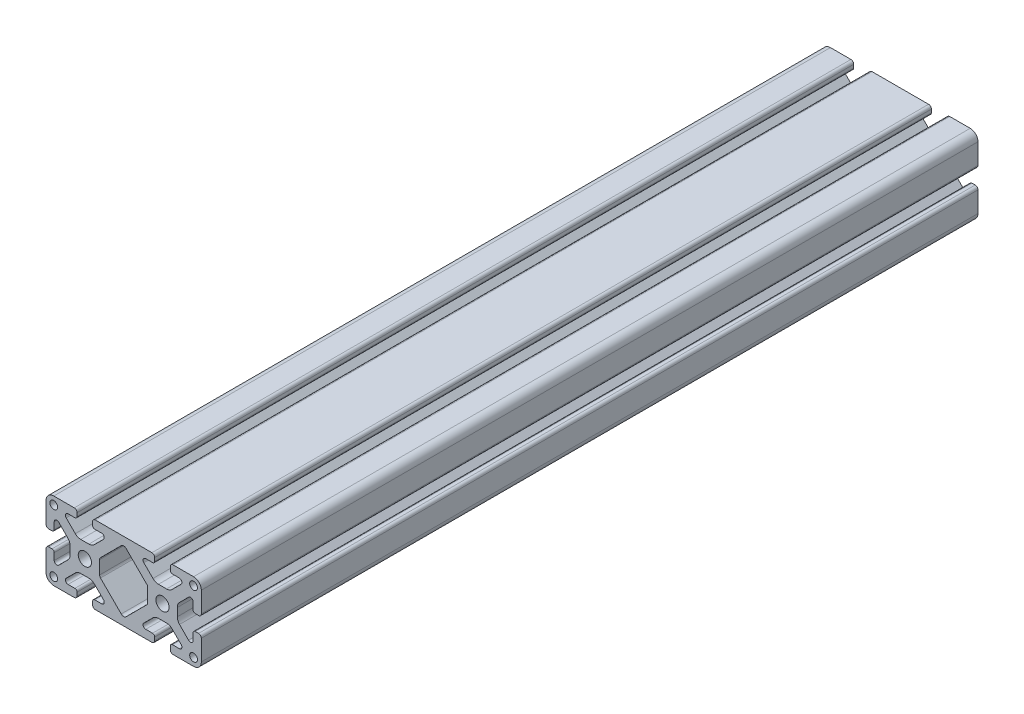
SolidWorks part; units mm, degrees
ref_plane "Front" through (0, 0, 0) normal (0, 0, 1) x (1, 0, 0)
ref_plane "Top" through (0, 0, 0) normal (0, 1, 0) x (1, 0, 0)
ref_plane "Right" through (0, 0, 0) normal (1, 0, 0) x (0, 0, -1)
sketch "Support-Front" plane through (0, 0, 0) normal (0, 0, 1) x (1, 0, 0)
  line L0 (50, 0) -> (-50, 0) construction
  line L1 (-50, -25) -> (50, -25)
  line L2 (-50, -25) -> (-50, 25)
  line L3 (-50, 25) -> (50, 25)
  line L4 (50, -25) -> (50, 25)
  line L5 (0, 25) -> (0, -25) construction
  dimension "Height-Profile" = 50
  dimension "Width-Profile" = 100
sketch "Support-Right-Length" plane through (0, 0, 0) normal (1, 0, 0) x (0, 0, -1)
  line L0 (0, -25) -> (0, 25) construction
  line L1 (-250, 25) -> (250, 25)
  line L2 (-250, 25) -> (-250, -25)
  line L3 (-250, -25) -> (250, -25)
  line L4 (250, 25) -> (250, -25)
  dimension "Length-Profile" = 500
sketch "Support-Profile" plane through (0, 0, 0) normal (0, 0, 1) x (1, 0, 0)
  line L12 (-14.9142, -5.6858) -> (-1.5556, -19.0444)
  line L13 (-15.5, 4.2716) -> (-15.5, -4.2716)
  line L14 (-1.5556, 19.0444) -> (-14.9142, 5.6858)
  line L15 (14.9142, 5.6858) -> (1.5556, 19.0444)
  line L16 (15.5, -4.2716) -> (15.5, 4.2716)
  line L17 (1.5556, -19.0444) -> (14.9142, -5.6858)
  line L104 (-30, -23.2) -> (-30, -21.1)
  line L105 (-31.4, -19.7) -> (-35.8, -19.7)
  line L106 (-36.9987, -16.7945) -> (-31.1255, -10.9545)
  line L107 (-27.6, -9.5) -> (-22.4, -9.5)
  line L108 (-18.8745, -10.9545) -> (-13.0013, -16.7945)
  line L109 (-14.2, -19.7) -> (-18.6, -19.7)
  line L110 (-20, -21.1) -> (-20, -23.2)
  line L111 (-18.2, -25) -> (18.2, -25)
  line L112 (20, -23.2) -> (20, -21.1)
  line L113 (18.6, -19.7) -> (14.2, -19.7)
  line L114 (13.0013, -16.7945) -> (18.8745, -10.9545)
  line L115 (22.4, -9.5) -> (27.6, -9.5)
  line L116 (31.1255, -10.9545) -> (36.9987, -16.7945)
  line L117 (35.8, -19.7) -> (31.4, -19.7)
  line L118 (30, -21.1) -> (30, -23.2)
  line L119 (31.8, -25) -> (45, -25)
  line L120 (50, -20) -> (50, -6.8)
  line L121 (48.2, -5) -> (46.1, -5)
  line L122 (44.7, -6.4) -> (44.7, -10.8)
  line L123 (41.7945, -11.9987) -> (35.9545, -6.1255)
  line L124 (34.5, -2.6) -> (34.5, 2.6)
  line L125 (35.9545, 6.1255) -> (41.7945, 11.9987)
  line L126 (44.7, 10.8) -> (44.7, 6.4)
  line L127 (46.1, 5) -> (48.2, 5)
  line L128 (50, 6.8) -> (50, 20)
  line L129 (45, 25) -> (31.8, 25)
  line L130 (30, 23.2) -> (30, 21.1)
  line L131 (31.4, 19.7) -> (35.8, 19.7)
  line L132 (36.9987, 16.7945) -> (31.1255, 10.9545)
  line L133 (27.6, 9.5) -> (22.4, 9.5)
  line L134 (18.8745, 10.9545) -> (13.0013, 16.7945)
  line L135 (14.2, 19.7) -> (18.6, 19.7)
  line L136 (20, 21.1) -> (20, 23.2)
  line L137 (18.2, 25) -> (-18.2, 25)
  line L138 (-20, 23.2) -> (-20, 21.1)
  line L139 (-18.6, 19.7) -> (-14.2, 19.7)
  line L140 (-13.0013, 16.7945) -> (-18.8745, 10.9545)
  line L141 (-22.4, 9.5) -> (-27.6, 9.5)
  line L142 (-31.1255, 10.9545) -> (-36.9987, 16.7945)
  line L143 (-35.8, 19.7) -> (-31.4, 19.7)
  line L144 (-30, 21.1) -> (-30, 23.2)
  line L145 (-31.8, 25) -> (-45, 25)
  line L146 (-50, 20) -> (-50, 6.8)
  line L147 (-48.2, 5) -> (-46.1, 5)
  line L148 (-44.7, 6.4) -> (-44.7, 10.8)
  line L149 (-41.7945, 11.9987) -> (-35.9545, 6.1255)
  line L150 (-34.5, 2.6) -> (-34.5, -2.6)
  line L151 (-35.9545, -6.1255) -> (-41.7945, -11.9987)
  line L152 (-44.7, -10.8) -> (-44.7, -6.4)
  line L153 (-46.1, -5) -> (-48.2, -5)
  line L154 (-50, -6.8) -> (-50, -20)
  line L155 (-45, -25) -> (-31.8, -25)
  circle A1 centre (-25, 0) radius 4.25
  circle A3 centre (-45, 20) radius 2.5
  circle A5 centre (-45, -20) radius 2.5
  arc A12 (-15.5, -4.2716) -> (-14.9142, -5.6858) centre (-13.5, -4.2716) ccw
  arc A13 (-14.9142, 5.6858) -> (-15.5, 4.2716) centre (-13.5, 4.2716) ccw
  arc A14 (1.5556, 19.0444) -> (-1.5556, 19.0444) centre (0, 17.4887) ccw
  arc A15 (15.5, 4.2716) -> (14.9142, 5.6858) centre (13.5, 4.2716) ccw
  arc A16 (14.9142, -5.6858) -> (15.5, -4.2716) centre (13.5, -4.2716) ccw
  arc A17 (-1.5556, -19.0444) -> (1.5556, -19.0444) centre (0, -17.4887) ccw
  circle A19 centre (25, 0) radius 4.25
  circle A21 centre (45, -20) radius 2.5
  circle A23 centre (45, 20) radius 2.5
  arc A104 (-30, -21.1) -> (-31.4, -19.7) centre (-31.4, -21.1) ccw
  arc A105 (-36.9987, -16.7945) -> (-35.8, -19.7) centre (-35.8, -18) ccw
  arc A106 (-27.6, -9.5) -> (-31.1255, -10.9545) centre (-27.6, -14.5) ccw
  arc A107 (-18.8745, -10.9545) -> (-22.4, -9.5) centre (-22.4, -14.5) ccw
  arc A108 (-14.2, -19.7) -> (-13.0013, -16.7945) centre (-14.2, -18) ccw
  arc A109 (-18.6, -19.7) -> (-20, -21.1) centre (-18.6, -21.1) ccw
  arc A110 (-20, -23.2) -> (-18.2, -25) centre (-18.2, -23.2) ccw
  arc A111 (18.2, -25) -> (20, -23.2) centre (18.2, -23.2) ccw
  arc A112 (20, -21.1) -> (18.6, -19.7) centre (18.6, -21.1) ccw
  arc A113 (13.0013, -16.7945) -> (14.2, -19.7) centre (14.2, -18) ccw
  arc A114 (22.4, -9.5) -> (18.8745, -10.9545) centre (22.4, -14.5) ccw
  arc A115 (31.1255, -10.9545) -> (27.6, -9.5) centre (27.6, -14.5) ccw
  arc A116 (35.8, -19.7) -> (36.9987, -16.7945) centre (35.8, -18) ccw
  arc A117 (31.4, -19.7) -> (30, -21.1) centre (31.4, -21.1) ccw
  arc A118 (30, -23.2) -> (31.8, -25) centre (31.8, -23.2) ccw
  arc A119 (45, -25) -> (50, -20) centre (45, -20) ccw
  arc A120 (50, -6.8) -> (48.2, -5) centre (48.2, -6.8) ccw
  arc A121 (46.1, -5) -> (44.7, -6.4) centre (46.1, -6.4) ccw
  arc A122 (41.7945, -11.9987) -> (44.7, -10.8) centre (43, -10.8) ccw
  arc A123 (34.5, -2.6) -> (35.9545, -6.1255) centre (39.5, -2.6) ccw
  arc A124 (35.9545, 6.1255) -> (34.5, 2.6) centre (39.5, 2.6) ccw
  arc A125 (44.7, 10.8) -> (41.7945, 11.9987) centre (43, 10.8) ccw
  arc A126 (44.7, 6.4) -> (46.1, 5) centre (46.1, 6.4) ccw
  arc A127 (48.2, 5) -> (50, 6.8) centre (48.2, 6.8) ccw
  arc A128 (50, 20) -> (45, 25) centre (45, 20) ccw
  arc A129 (31.8, 25) -> (30, 23.2) centre (31.8, 23.2) ccw
  arc A130 (30, 21.1) -> (31.4, 19.7) centre (31.4, 21.1) ccw
  arc A131 (36.9987, 16.7945) -> (35.8, 19.7) centre (35.8, 18) ccw
  arc A132 (27.6, 9.5) -> (31.1255, 10.9545) centre (27.6, 14.5) ccw
  arc A133 (18.8745, 10.9545) -> (22.4, 9.5) centre (22.4, 14.5) ccw
  arc A134 (14.2, 19.7) -> (13.0013, 16.7945) centre (14.2, 18) ccw
  arc A135 (18.6, 19.7) -> (20, 21.1) centre (18.6, 21.1) ccw
  arc A136 (20, 23.2) -> (18.2, 25) centre (18.2, 23.2) ccw
  arc A137 (-18.2, 25) -> (-20, 23.2) centre (-18.2, 23.2) ccw
  arc A138 (-20, 21.1) -> (-18.6, 19.7) centre (-18.6, 21.1) ccw
  arc A139 (-13.0013, 16.7945) -> (-14.2, 19.7) centre (-14.2, 18) ccw
  arc A140 (-22.4, 9.5) -> (-18.8745, 10.9545) centre (-22.4, 14.5) ccw
  arc A141 (-31.1255, 10.9545) -> (-27.6, 9.5) centre (-27.6, 14.5) ccw
  arc A142 (-35.8, 19.7) -> (-36.9987, 16.7945) centre (-35.8, 18) ccw
  arc A143 (-31.4, 19.7) -> (-30, 21.1) centre (-31.4, 21.1) ccw
  arc A144 (-30, 23.2) -> (-31.8, 25) centre (-31.8, 23.2) ccw
  arc A145 (-45, 25) -> (-50, 20) centre (-45, 20) ccw
  arc A146 (-50, 6.8) -> (-48.2, 5) centre (-48.2, 6.8) ccw
  arc A147 (-46.1, 5) -> (-44.7, 6.4) centre (-46.1, 6.4) ccw
  arc A148 (-41.7945, 11.9987) -> (-44.7, 10.8) centre (-43, 10.8) ccw
  arc A149 (-34.5, 2.6) -> (-35.9545, 6.1255) centre (-39.5, 2.6) ccw
  arc A150 (-35.9545, -6.1255) -> (-34.5, -2.6) centre (-39.5, -2.6) ccw
  arc A151 (-44.7, -10.8) -> (-41.7945, -11.9987) centre (-43, -10.8) ccw
  arc A152 (-44.7, -6.4) -> (-46.1, -5) centre (-46.1, -6.4) ccw
  arc A153 (-48.2, -5) -> (-50, -6.8) centre (-48.2, -6.8) ccw
  arc A154 (-50, -20) -> (-45, -25) centre (-45, -20) ccw
  arc A155 (-31.8, -25) -> (-30, -23.2) centre (-31.8, -23.2) ccw
ref_plane "Ref-Plane-1" through (0, 0, 250) normal (0, 0, 1) x (1, 0, 0)
ref_plane "Ref-Plane-2" through (0, 0, -250) normal (0, 0, 1) x (1, 0, 0)
sketch "Sketch4" plane through (0, 0, 250) normal (0, 0, 1) x (1, 0, 0)
  line L0 (-50, -25) -> (-50, 25) construction
  line L1 (-50, -25) -> (50, -25) construction
  line L2 (50, -25) -> (50, 25) construction
  line L3 (-50, 25) -> (50, 25) construction
  line L4 (-50, -25) -> (-50, 25)
  line L5 (-50, -25) -> (50, -25)
  line L6 (50, -25) -> (50, 25)
  line L7 (-50, 25) -> (50, 25)
extrude "Body" add sketch "Sketch4" against normal up to surface (500 mm away) up to plane "Ref-Plane-2"
sketch "Sketch6" plane through (0, 0, 0) normal (0, 0, 1) x (1, 0, 0)
  line L6 (14.9142, 5.6858) -> (1.5556, 19.0444)
  line L7 (-1.5556, 19.0444) -> (-14.9142, 5.6858)
  line L8 (-15.5, 4.2716) -> (-15.5, -4.2716)
  line L9 (-14.9142, -5.6858) -> (-1.5556, -19.0444)
  line L10 (1.5556, -19.0444) -> (14.9142, -5.6858)
  line L11 (15.5, -4.2716) -> (15.5, 4.2716)
  line L12 (14.9142, 5.6858) -> (1.5556, 19.0444)
  line L13 (-1.5556, 19.0444) -> (-14.9142, 5.6858)
  line L14 (-15.5, 4.2716) -> (-15.5, -4.2716)
  line L15 (-14.9142, -5.6858) -> (-1.5556, -19.0444)
  line L16 (1.5556, -19.0444) -> (14.9142, -5.6858)
  line L17 (15.5, -4.2716) -> (15.5, 4.2716)
  line L52 (-31.4, -19.7) -> (-35.8, -19.7)
  line L53 (-36.9987, -16.7945) -> (-31.1255, -10.9545)
  line L54 (-27.6, -9.5) -> (-22.4, -9.5)
  line L55 (-18.8745, -10.9545) -> (-13.0013, -16.7945)
  line L56 (-14.2, -19.7) -> (-18.6, -19.7)
  line L57 (-20, -21.1) -> (-20, -23.2)
  line L58 (-18.2, -25) -> (18.2, -25)
  line L59 (20, -23.2) -> (20, -21.1)
  line L60 (18.6, -19.7) -> (14.2, -19.7)
  line L61 (13.0013, -16.7945) -> (18.8745, -10.9545)
  line L62 (22.4, -9.5) -> (27.6, -9.5)
  line L63 (31.1255, -10.9545) -> (36.9987, -16.7945)
  line L64 (35.8, -19.7) -> (31.4, -19.7)
  line L65 (30, -21.1) -> (30, -23.2)
  line L66 (31.8, -25) -> (45, -25)
  line L67 (50, -20) -> (50, -6.8)
  line L68 (48.2, -5) -> (46.1, -5)
  line L69 (44.7, -6.4) -> (44.7, -10.8)
  line L70 (41.7945, -11.9987) -> (35.9545, -6.1255)
  line L71 (34.5, -2.6) -> (34.5, 2.6)
  line L72 (35.9545, 6.1255) -> (41.7945, 11.9987)
  line L73 (44.7, 10.8) -> (44.7, 6.4)
  line L74 (46.1, 5) -> (48.2, 5)
  line L75 (50, 6.8) -> (50, 20)
  line L76 (45, 25) -> (31.8, 25)
  line L77 (30, 23.2) -> (30, 21.1)
  line L78 (31.4, 19.7) -> (35.8, 19.7)
  line L79 (36.9987, 16.7945) -> (31.1255, 10.9545)
  line L80 (27.6, 9.5) -> (22.4, 9.5)
  line L81 (18.8745, 10.9545) -> (13.0013, 16.7945)
  line L82 (14.2, 19.7) -> (18.6, 19.7)
  line L83 (20, 21.1) -> (20, 23.2)
  line L84 (18.2, 25) -> (-18.2, 25)
  line L85 (-20, 23.2) -> (-20, 21.1)
  line L86 (-18.6, 19.7) -> (-14.2, 19.7)
  line L87 (-13.0013, 16.7945) -> (-18.8745, 10.9545)
  line L88 (-22.4, 9.5) -> (-27.6, 9.5)
  line L89 (-31.1255, 10.9545) -> (-36.9987, 16.7945)
  line L90 (-35.8, 19.7) -> (-31.4, 19.7)
  line L91 (-30, 21.1) -> (-30, 23.2)
  line L92 (-31.8, 25) -> (-45, 25)
  line L93 (-50, 20) -> (-50, 6.8)
  line L94 (-48.2, 5) -> (-46.1, 5)
  line L95 (-44.7, 6.4) -> (-44.7, 10.8)
  line L96 (-41.7945, 11.9987) -> (-35.9545, 6.1255)
  line L97 (-34.5, 2.6) -> (-34.5, -2.6)
  line L98 (-35.9545, -6.1255) -> (-41.7945, -11.9987)
  line L99 (-44.7, -10.8) -> (-44.7, -6.4)
  line L100 (-46.1, -5) -> (-48.2, -5)
  line L101 (-50, -6.8) -> (-50, -20)
  line L102 (-45, -25) -> (-31.8, -25)
  line L103 (-30, -23.2) -> (-30, -21.1)
  line L104 (-31.4, -19.7) -> (-35.8, -19.7)
  line L105 (-36.9987, -16.7945) -> (-31.1255, -10.9545)
  line L106 (-27.6, -9.5) -> (-22.4, -9.5)
  line L107 (-18.8745, -10.9545) -> (-13.0013, -16.7945)
  line L108 (-14.2, -19.7) -> (-18.6, -19.7)
  line L109 (-20, -21.1) -> (-20, -23.2)
  line L110 (-18.2, -25) -> (18.2, -25)
  line L111 (20, -23.2) -> (20, -21.1)
  line L112 (18.6, -19.7) -> (14.2, -19.7)
  line L113 (13.0013, -16.7945) -> (18.8745, -10.9545)
  line L114 (22.4, -9.5) -> (27.6, -9.5)
  line L115 (31.1255, -10.9545) -> (36.9987, -16.7945)
  line L116 (35.8, -19.7) -> (31.4, -19.7)
  line L117 (30, -21.1) -> (30, -23.2)
  line L118 (31.8, -25) -> (45, -25)
  line L119 (50, -20) -> (50, -6.8)
  line L120 (48.2, -5) -> (46.1, -5)
  line L121 (44.7, -6.4) -> (44.7, -10.8)
  line L122 (41.7945, -11.9987) -> (35.9545, -6.1255)
  line L123 (34.5, -2.6) -> (34.5, 2.6)
  line L124 (35.9545, 6.1255) -> (41.7945, 11.9987)
  line L125 (44.7, 10.8) -> (44.7, 6.4)
  line L126 (46.1, 5) -> (48.2, 5)
  line L127 (50, 6.8) -> (50, 20)
  line L128 (45, 25) -> (31.8, 25)
  line L129 (30, 23.2) -> (30, 21.1)
  line L130 (31.4, 19.7) -> (35.8, 19.7)
  line L131 (36.9987, 16.7945) -> (31.1255, 10.9545)
  line L132 (27.6, 9.5) -> (22.4, 9.5)
  line L133 (18.8745, 10.9545) -> (13.0013, 16.7945)
  line L134 (14.2, 19.7) -> (18.6, 19.7)
  line L135 (20, 21.1) -> (20, 23.2)
  line L136 (18.2, 25) -> (-18.2, 25)
  line L137 (-20, 23.2) -> (-20, 21.1)
  line L138 (-18.6, 19.7) -> (-14.2, 19.7)
  line L139 (-13.0013, 16.7945) -> (-18.8745, 10.9545)
  line L140 (-22.4, 9.5) -> (-27.6, 9.5)
  line L141 (-31.1255, 10.9545) -> (-36.9987, 16.7945)
  line L142 (-35.8, 19.7) -> (-31.4, 19.7)
  line L143 (-30, 21.1) -> (-30, 23.2)
  line L144 (-31.8, 25) -> (-45, 25)
  line L145 (-50, 20) -> (-50, 6.8)
  line L146 (-48.2, 5) -> (-46.1, 5)
  line L147 (-44.7, 6.4) -> (-44.7, 10.8)
  line L148 (-41.7945, 11.9987) -> (-35.9545, 6.1255)
  line L149 (-34.5, 2.6) -> (-34.5, -2.6)
  line L150 (-35.9545, -6.1255) -> (-41.7945, -11.9987)
  line L151 (-44.7, -10.8) -> (-44.7, -6.4)
  line L152 (-46.1, -5) -> (-48.2, -5)
  line L153 (-50, -6.8) -> (-50, -20)
  line L154 (-45, -25) -> (-31.8, -25)
  line L155 (-30, -23.2) -> (-30, -21.1)
  circle A0 centre (25, 0) radius 4.25 construction
  circle A1 centre (45, -20) radius 2.5 construction
  circle A2 centre (45, 20) radius 2.5 construction
  circle A3 centre (-45, -20) radius 2.5 construction
  circle A4 centre (-45, 20) radius 2.5 construction
  circle A5 centre (-25, 0) radius 4.25 construction
  circle A6 centre (25, 0) radius 4.25
  circle A7 centre (45, -20) radius 2.5
  circle A8 centre (45, 20) radius 2.5
  circle A9 centre (-45, -20) radius 2.5
  circle A10 centre (-45, 20) radius 2.5
  circle A11 centre (-25, 0) radius 4.25
  arc A18 (1.5556, 19.0444) -> (-1.5556, 19.0444) centre (0, 17.4887) ccw
  arc A19 (-14.9142, 5.6858) -> (-15.5, 4.2716) centre (-13.5, 4.2716) ccw
  arc A20 (-15.5, -4.2716) -> (-14.9142, -5.6858) centre (-13.5, -4.2716) ccw
  arc A21 (-1.5556, -19.0444) -> (1.5556, -19.0444) centre (0, -17.4887) ccw
  arc A22 (14.9142, -5.6858) -> (15.5, -4.2716) centre (13.5, -4.2716) ccw
  arc A23 (15.5, 4.2716) -> (14.9142, 5.6858) centre (13.5, 4.2716) ccw
  arc A24 (1.5556, 19.0444) -> (-1.5556, 19.0444) centre (0, 17.4887) ccw
  arc A25 (-14.9142, 5.6858) -> (-15.5, 4.2716) centre (-13.5, 4.2716) ccw
  arc A26 (-15.5, -4.2716) -> (-14.9142, -5.6858) centre (-13.5, -4.2716) ccw
  arc A27 (-1.5556, -19.0444) -> (1.5556, -19.0444) centre (0, -17.4887) ccw
  arc A28 (14.9142, -5.6858) -> (15.5, -4.2716) centre (13.5, -4.2716) ccw
  arc A29 (15.5, 4.2716) -> (14.9142, 5.6858) centre (13.5, 4.2716) ccw
  arc A52 (-36.9987, -16.7945) -> (-35.8, -19.7) centre (-35.8, -18) ccw
  arc A53 (-27.6, -9.5) -> (-31.1255, -10.9545) centre (-27.6, -14.5) ccw
  arc A54 (-18.8745, -10.9545) -> (-22.4, -9.5) centre (-22.4, -14.5) ccw
  arc A55 (-14.2, -19.7) -> (-13.0013, -16.7945) centre (-14.2, -18) ccw
  arc A56 (-18.6, -19.7) -> (-20, -21.1) centre (-18.6, -21.1) ccw
  arc A57 (-20, -23.2) -> (-18.2, -25) centre (-18.2, -23.2) ccw
  arc A59 (18.2, -25) -> (20, -23.2) centre (18.2, -23.2) ccw
  arc A60 (20, -21.1) -> (18.6, -19.7) centre (18.6, -21.1) ccw
  arc A61 (13.0013, -16.7945) -> (14.2, -19.7) centre (14.2, -18) ccw
  arc A62 (22.4, -9.5) -> (18.8745, -10.9545) centre (22.4, -14.5) ccw
  arc A63 (31.1255, -10.9545) -> (27.6, -9.5) centre (27.6, -14.5) ccw
  arc A64 (35.8, -19.7) -> (36.9987, -16.7945) centre (35.8, -18) ccw
  arc A65 (31.4, -19.7) -> (30, -21.1) centre (31.4, -21.1) ccw
  arc A66 (30, -23.2) -> (31.8, -25) centre (31.8, -23.2) ccw
  arc A67 (45, -25) -> (50, -20) centre (45, -20) ccw
  arc A68 (50, -6.8) -> (48.2, -5) centre (48.2, -6.8) ccw
  arc A69 (46.1, -5) -> (44.7, -6.4) centre (46.1, -6.4) ccw
  arc A70 (41.7945, -11.9987) -> (44.7, -10.8) centre (43, -10.8) ccw
  arc A71 (34.5, -2.6) -> (35.9545, -6.1255) centre (39.5, -2.6) ccw
  arc A72 (35.9545, 6.1255) -> (34.5, 2.6) centre (39.5, 2.6) ccw
  arc A73 (44.7, 10.8) -> (41.7945, 11.9987) centre (43, 10.8) ccw
  arc A74 (44.7, 6.4) -> (46.1, 5) centre (46.1, 6.4) ccw
  arc A75 (48.2, 5) -> (50, 6.8) centre (48.2, 6.8) ccw
  arc A76 (50, 20) -> (45, 25) centre (45, 20) ccw
  arc A77 (31.8, 25) -> (30, 23.2) centre (31.8, 23.2) ccw
  arc A78 (30, 21.1) -> (31.4, 19.7) centre (31.4, 21.1) ccw
  arc A79 (36.9987, 16.7945) -> (35.8, 19.7) centre (35.8, 18) ccw
  arc A80 (27.6, 9.5) -> (31.1255, 10.9545) centre (27.6, 14.5) ccw
  arc A81 (18.8745, 10.9545) -> (22.4, 9.5) centre (22.4, 14.5) ccw
  arc A82 (14.2, 19.7) -> (13.0013, 16.7945) centre (14.2, 18) ccw
  arc A83 (18.6, 19.7) -> (20, 21.1) centre (18.6, 21.1) ccw
  arc A84 (20, 23.2) -> (18.2, 25) centre (18.2, 23.2) ccw
  arc A85 (-18.2, 25) -> (-20, 23.2) centre (-18.2, 23.2) ccw
  arc A86 (-20, 21.1) -> (-18.6, 19.7) centre (-18.6, 21.1) ccw
  arc A87 (-13.0013, 16.7945) -> (-14.2, 19.7) centre (-14.2, 18) ccw
  arc A88 (-22.4, 9.5) -> (-18.8745, 10.9545) centre (-22.4, 14.5) ccw
  arc A89 (-31.1255, 10.9545) -> (-27.6, 9.5) centre (-27.6, 14.5) ccw
  arc A90 (-35.8, 19.7) -> (-36.9987, 16.7945) centre (-35.8, 18) ccw
  arc A91 (-31.4, 19.7) -> (-30, 21.1) centre (-31.4, 21.1) ccw
  arc A92 (-30, 23.2) -> (-31.8, 25) centre (-31.8, 23.2) ccw
  arc A93 (-45, 25) -> (-50, 20) centre (-45, 20) ccw
  arc A94 (-50, 6.8) -> (-48.2, 5) centre (-48.2, 6.8) ccw
  arc A95 (-46.1, 5) -> (-44.7, 6.4) centre (-46.1, 6.4) ccw
  arc A96 (-41.7945, 11.9987) -> (-44.7, 10.8) centre (-43, 10.8) ccw
  arc A97 (-34.5, 2.6) -> (-35.9545, 6.1255) centre (-39.5, 2.6) ccw
  arc A98 (-35.9545, -6.1255) -> (-34.5, -2.6) centre (-39.5, -2.6) ccw
  arc A99 (-44.7, -10.8) -> (-41.7945, -11.9987) centre (-43, -10.8) ccw
  arc A100 (-44.7, -6.4) -> (-46.1, -5) centre (-46.1, -6.4) ccw
  arc A101 (-48.2, -5) -> (-50, -6.8) centre (-48.2, -6.8) ccw
  arc A102 (-50, -20) -> (-45, -25) centre (-45, -20) ccw
  arc A103 (-31.8, -25) -> (-30, -23.2) centre (-31.8, -23.2) ccw
  arc A104 (-30, -21.1) -> (-31.4, -19.7) centre (-31.4, -21.1) ccw
  arc A105 (-36.9987, -16.7945) -> (-35.8, -19.7) centre (-35.8, -18) ccw
  arc A106 (-27.6, -9.5) -> (-31.1255, -10.9545) centre (-27.6, -14.5) ccw
  arc A107 (-18.8745, -10.9545) -> (-22.4, -9.5) centre (-22.4, -14.5) ccw
  arc A108 (-14.2, -19.7) -> (-13.0013, -16.7945) centre (-14.2, -18) ccw
  arc A109 (-18.6, -19.7) -> (-20, -21.1) centre (-18.6, -21.1) ccw
  arc A110 (-20, -23.2) -> (-18.2, -25) centre (-18.2, -23.2) ccw
  arc A111 (18.2, -25) -> (20, -23.2) centre (18.2, -23.2) ccw
  arc A112 (20, -21.1) -> (18.6, -19.7) centre (18.6, -21.1) ccw
  arc A113 (13.0013, -16.7945) -> (14.2, -19.7) centre (14.2, -18) ccw
  arc A114 (22.4, -9.5) -> (18.8745, -10.9545) centre (22.4, -14.5) ccw
  arc A115 (31.1255, -10.9545) -> (27.6, -9.5) centre (27.6, -14.5) ccw
  arc A116 (35.8, -19.7) -> (36.9987, -16.7945) centre (35.8, -18) ccw
  arc A117 (31.4, -19.7) -> (30, -21.1) centre (31.4, -21.1) ccw
  arc A118 (30, -23.2) -> (31.8, -25) centre (31.8, -23.2) ccw
  arc A119 (45, -25) -> (50, -20) centre (45, -20) ccw
  arc A120 (50, -6.8) -> (48.2, -5) centre (48.2, -6.8) ccw
  arc A121 (46.1, -5) -> (44.7, -6.4) centre (46.1, -6.4) ccw
  arc A122 (41.7945, -11.9987) -> (44.7, -10.8) centre (43, -10.8) ccw
  arc A123 (34.5, -2.6) -> (35.9545, -6.1255) centre (39.5, -2.6) ccw
  arc A124 (35.9545, 6.1255) -> (34.5, 2.6) centre (39.5, 2.6) ccw
  arc A125 (44.7, 10.8) -> (41.7945, 11.9987) centre (43, 10.8) ccw
  arc A126 (44.7, 6.4) -> (46.1, 5) centre (46.1, 6.4) ccw
  arc A127 (48.2, 5) -> (50, 6.8) centre (48.2, 6.8) ccw
  arc A128 (50, 20) -> (45, 25) centre (45, 20) ccw
  arc A129 (31.8, 25) -> (30, 23.2) centre (31.8, 23.2) ccw
  arc A130 (30, 21.1) -> (31.4, 19.7) centre (31.4, 21.1) ccw
  arc A131 (36.9987, 16.7945) -> (35.8, 19.7) centre (35.8, 18) ccw
  arc A132 (27.6, 9.5) -> (31.1255, 10.9545) centre (27.6, 14.5) ccw
  arc A133 (18.8745, 10.9545) -> (22.4, 9.5) centre (22.4, 14.5) ccw
  arc A134 (14.2, 19.7) -> (13.0013, 16.7945) centre (14.2, 18) ccw
  arc A135 (18.6, 19.7) -> (20, 21.1) centre (18.6, 21.1) ccw
  arc A136 (20, 23.2) -> (18.2, 25) centre (18.2, 23.2) ccw
  arc A137 (-18.2, 25) -> (-20, 23.2) centre (-18.2, 23.2) ccw
  arc A138 (-20, 21.1) -> (-18.6, 19.7) centre (-18.6, 21.1) ccw
  arc A139 (-13.0013, 16.7945) -> (-14.2, 19.7) centre (-14.2, 18) ccw
  arc A140 (-22.4, 9.5) -> (-18.8745, 10.9545) centre (-22.4, 14.5) ccw
  arc A141 (-31.1255, 10.9545) -> (-27.6, 9.5) centre (-27.6, 14.5) ccw
  arc A142 (-35.8, 19.7) -> (-36.9987, 16.7945) centre (-35.8, 18) ccw
  arc A143 (-31.4, 19.7) -> (-30, 21.1) centre (-31.4, 21.1) ccw
  arc A144 (-30, 23.2) -> (-31.8, 25) centre (-31.8, 23.2) ccw
  arc A145 (-45, 25) -> (-50, 20) centre (-45, 20) ccw
  arc A146 (-50, 6.8) -> (-48.2, 5) centre (-48.2, 6.8) ccw
  arc A147 (-46.1, 5) -> (-44.7, 6.4) centre (-46.1, 6.4) ccw
  arc A148 (-41.7945, 11.9987) -> (-44.7, 10.8) centre (-43, 10.8) ccw
  arc A149 (-34.5, 2.6) -> (-35.9545, 6.1255) centre (-39.5, 2.6) ccw
  arc A150 (-35.9545, -6.1255) -> (-34.5, -2.6) centre (-39.5, -2.6) ccw
  arc A151 (-44.7, -10.8) -> (-41.7945, -11.9987) centre (-43, -10.8) ccw
  arc A152 (-44.7, -6.4) -> (-46.1, -5) centre (-46.1, -6.4) ccw
  arc A153 (-48.2, -5) -> (-50, -6.8) centre (-48.2, -6.8) ccw
  arc A154 (-50, -20) -> (-45, -25) centre (-45, -20) ccw
  arc A155 (-31.8, -25) -> (-30, -23.2) centre (-31.8, -23.2) ccw
  arc A156 (-30, -21.1) -> (-31.4, -19.7) centre (-31.4, -21.1) ccw
  dimension "D1" = 0
  dimension "D2" = 0
extrude "Cut-Profile" cut sketch "Sketch6" against normal through all and the other way through all flip side to cut
